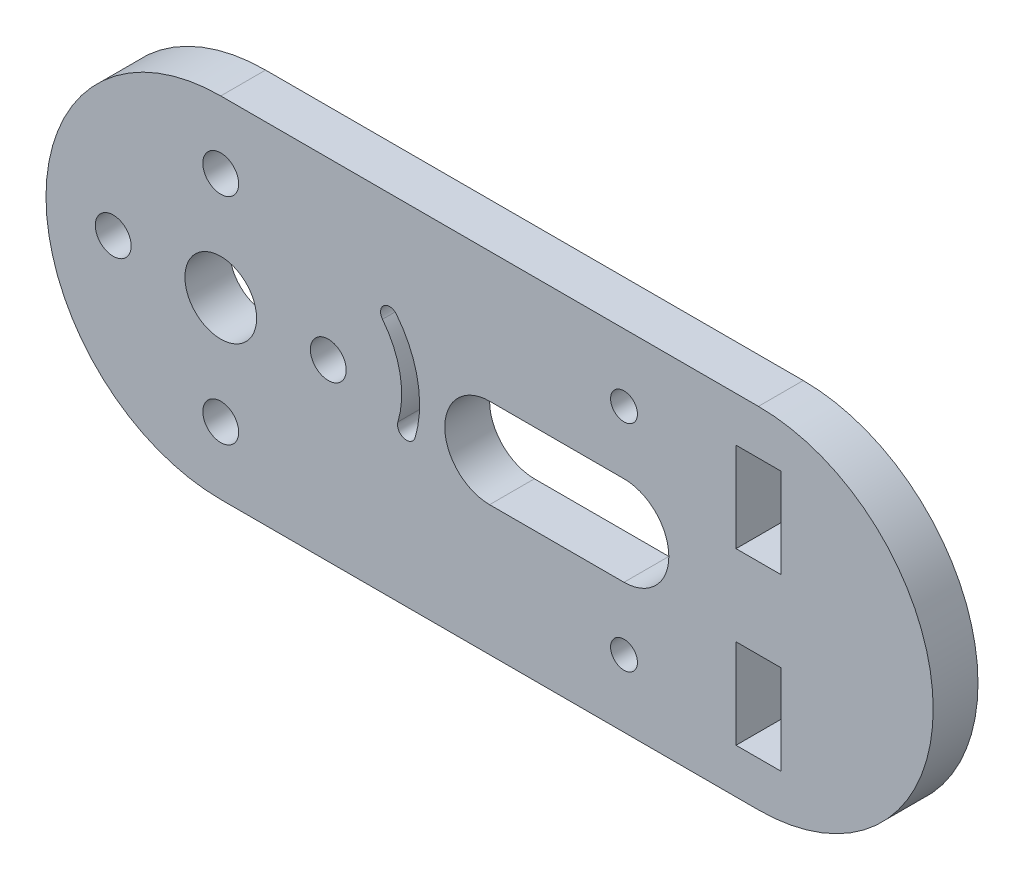
SolidWorks part; units mm, degrees
ref_plane "Front Plane" through (0, 0, 0) normal (0, 0, 1) x (1, 0, 0)
ref_plane "Top Plane" through (0, 0, 0) normal (0, 1, 0) x (1, 0, 0)
ref_plane "Right Plane" through (0, 0, 0) normal (1, 0, 0) x (0, 0, -1)
sketch "Sketch1" plane through (0, 0, 0) normal (0, 0, 1) x (1, 0, 0)
  line L0 (-30, 0) -> (30, 0) construction
  line L1 (15, -12) -> (15, 0) construction
  line L2 (-30, 19.5) -> (30, 19.5)
  line L3 (-30, -19.5) -> (30, -19.5)
  line L4 (15, 0) -> (0, 0) construction
  line L5 (-19.8084, 0.7599) -> (-11.9503, 6.9445) construction
  line L6 (15, -5) -> (0, -5)
  line L7 (15, 5) -> (0, 5)
  line L8 (-19.8084, 0.7599) -> (-10.2317, -2.1188) construction
  line L9 (30, 19.5) -> (30, 14.5) construction
  line L10 (30, -19.5) -> (30, -14.5) construction
  line L11 (27.5, 14.5) -> (32.5, 14.5)
  line L12 (32.5, 14.5) -> (32.5, 4.5)
  line L13 (32.5, 4.5) -> (27.5, 4.5)
  line L14 (27.5, 4.5) -> (27.5, 14.5)
  line L15 (27.5, -14.5) -> (32.5, -14.5)
  line L16 (32.5, -14.5) -> (32.5, -4.5)
  line L17 (32.5, -4.5) -> (27.5, -4.5)
  line L18 (27.5, -4.5) -> (27.5, -14.5)
  arc A0 (-30, 19.5) -> (-30, -19.5) centre (-30, 0) ccw
  arc A1 (30, -19.5) -> (30, 19.5) centre (30, 0) ccw
  circle A3 centre (-30, 12) radius 2
  circle A4 centre (-18, 0) radius 2
  circle A5 centre (-30, -12) radius 2
  circle A6 centre (-42, 0) radius 2
  circle A7 centre (-30, 0) radius 4
  circle A8 centre (15, 12) radius 1.5
  circle A9 centre (15, -12) radius 1.5
  arc A10 (15, -5) -> (15, 5) centre (15, 0) ccw
  arc A11 (0, 5) -> (0, -5) centre (0, 0) ccw
  arc A16 (-11.9503, 6.9445) -> (-10.3787, 8.1815) centre (-11.1645, 7.563) cw
  arc A17 (-10.2317, -2.1188) -> (-8.3164, -2.6946) centre (-9.2741, -2.4067) ccw
  arc A18 (-10.2317, -2.1188) -> (-11.9503, 6.9445) centre (-19.8084, 0.7599) ccw
  arc A19 (-8.3164, -2.6946) -> (-10.3787, 8.1815) centre (-19.8084, 0.7599) ccw
  point P5 (0, 0)
  point P26 (7.5, 0)
  point P35 (-19.8084, 0.7599)
  point P37 (-49.5, 0)
  point P45 (30, 14.5)
  point P50 (30, -14.5)
  dimension "D1" = 39
  dimension "D3" = 4
  dimension "D4" = 4
  dimension "D5" = 4
  dimension "D6" = 4
  dimension "D11" = 8
  dimension "D12" = 3
  dimension "D14" = 3
  dimension "D19" = 5
  dimension "D20" = 5
  dimension "D21" = 29.7013
  dimension "D22" = 1
  dimension "D23" = 1
  dimension "D2" = 60
  dimension "D7" = 12
  dimension "D8" = 12
  dimension "D9" = 12
  dimension "D10" = 12
  dimension "D13" = 45
  dimension "D15" = 45
  dimension "D16" = 12
  dimension "D17" = 10
  dimension "D18" = 15
  dimension "D24" = 10
  dimension "D25" = 5
  dimension "D26" = 5
  dimension "D27" = 10
extrude "Boss-Extrude1" add sketch "Sketch1" along normal blind 5
